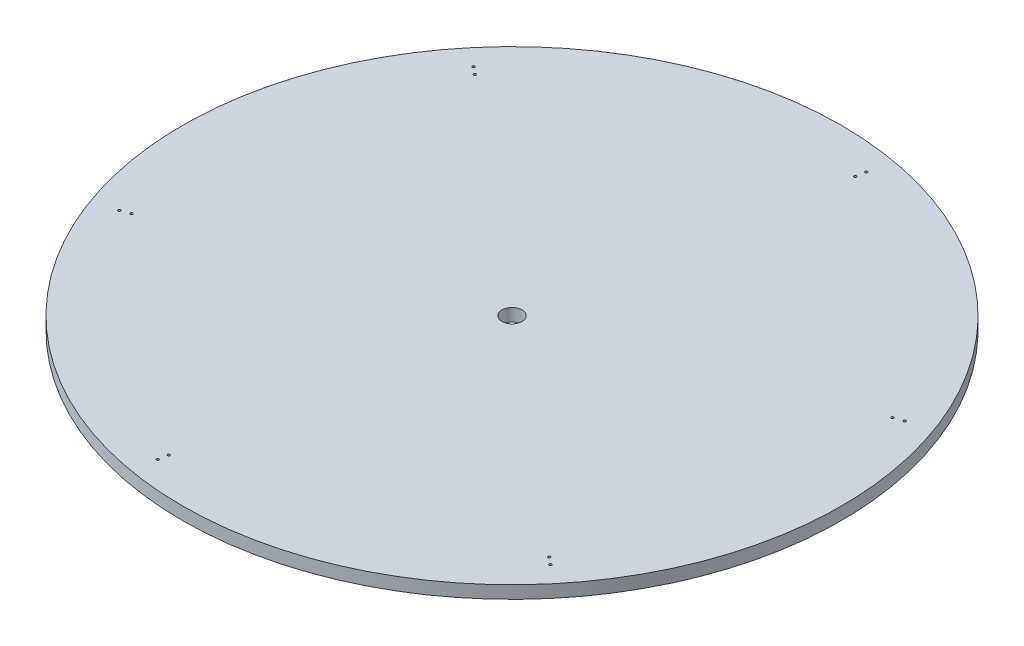
SolidWorks part; units mm, degrees
material "Oak"
ref_plane "Front Plane" through (0, 0, 0) normal (0, 0, 1) x (1, 0, 0)
ref_plane "Top Plane" through (0, 0, 0) normal (0, 1, 0) x (1, 0, 0)
ref_plane "Right Plane" through (0, 0, 0) normal (1, 0, 0) x (0, 0, -1)
sketch "Sketch1" plane through (0, 0, 0) normal (0, 1, 0) x (1, 0, 0)
  circle A0 centre (0, 0) radius 520
extrude "Boss-Extrude2" add sketch "Sketch1" along normal blind 20 contours A0
sketch "Sketch5" plane through (0, 20, 0) normal (0, 1, 0) x (1, 0, 0)
  line L0 (0, 0) -> (-488.3701, -178.5906) construction
  circle A0 centre (0, 0) radius 15.875
  circle A1 centre (-439.531, -160.7373) radius 2.0071
  circle A2 centre (0, 0) radius 520 construction
  circle A3 centre (-453.6207, -165.8832) radius 2
  dimension "D1" = 468
  dimension "D2" = 15
  dimension "D3" = 31.75
extrude "Cut-Extrude2" cut sketch "Sketch5" against normal blind 80 and the other way blind 71
pattern_circular "CirPattern6" count 6 over 360 about axis through (0, 0, 0) along (0, 1, 0) of "Cut-Extrude2"
